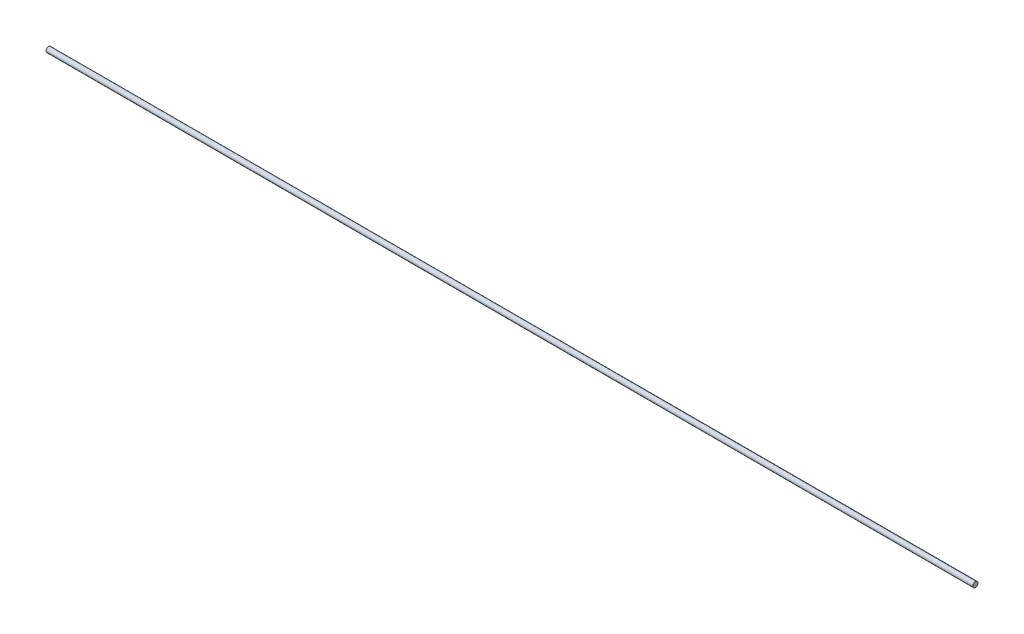
SolidWorks part; units mm, degrees
ref_plane "Front Plane" through (0, 0, 0) normal (0, 0, 1) x (1, 0, 0)
ref_plane "Top Plane" through (0, 0, 0) normal (0, 1, 0) x (1, 0, 0)
ref_plane "Right Plane" through (0, 0, 0) normal (1, 0, 0) x (0, 0, -1)
sketch "Sketch1" plane through (0, 0, 0) normal (1, 0, 0) x (0, 0, -1)
  circle A0 centre (0, 0) radius 3
extrude "Boss-Extrude1" add sketch "Sketch1" along normal blind 1080
